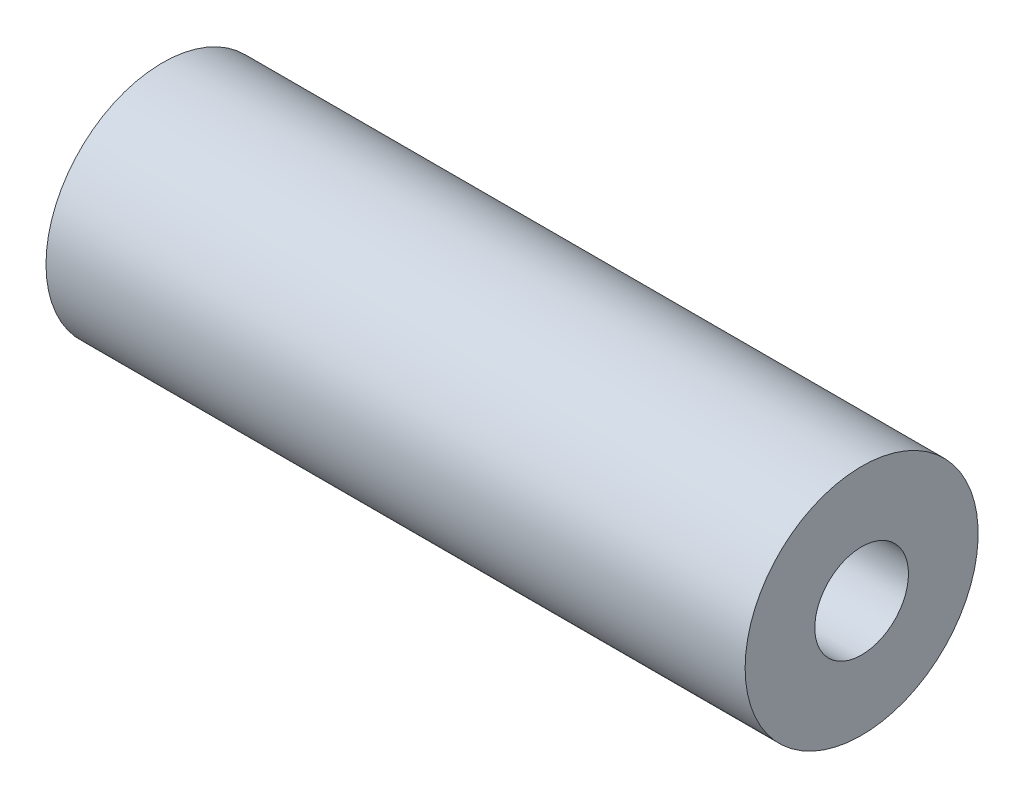
SolidWorks part; units mm, degrees
ref_plane "Front Plane" through (0, 0, 0) normal (0, 0, 1) x (1, 0, 0)
ref_plane "Top Plane" through (0, 0, 0) normal (0, 1, 0) x (1, 0, 0)
ref_plane "Right Plane" through (0, 0, 0) normal (1, 0, 0) x (0, 0, -1)
sketch "Sketch1" plane through (0, 0, 0) normal (1, 0, 0) x (0, 0, -1)
  circle A1 centre (0, 0) radius 6.35
  dimension "D1" = 12.7
extrude "Boss-Extrude1" add sketch "Sketch1" along normal blind 38.1
hole_wizard "Tap Drill for 1/4-20 Tap1" positions "Sketch3" profile "Sketch4" hole size "1/4-20" standard "ANSI Inch"
sketch "Sketch3" plane through (0, 0, 0) normal (-1, 0, 0) x (0, 0, 1)
  point P0 (0, 0)
sketch "Sketch4" plane through (0, 0, 0) normal (0, 1, 0) x (0, 0, 1)
  line L0 (0, 0) -> (0, 14.2338)
  line L1 (0, 14.2338) -> (2.5527, 12.7)
  line L2 (2.5527, 12.7) -> (2.5527, 0)
  line L5 (2.5527, 0) -> (0, 0)
  line L10 (0, 14.2338) -> (-2.5527, 12.7) construction
  line L11 (0, -6.35) -> (0, 107.95) construction
  dimension "Hole Dia." = 5.1054
  dimension "Hole Depth" = 12.7
  dimension "Drill Angle" = 118
ref_plane "Plane1" through (19.05, 0, 0) normal (-1, 0, 0) x (0, 0, 1)
mirror "Mirror1" about plane through (19.05, 0, 0) normal (-1, 0, 0) of "Tap Drill for 1/4-20 Tap1"
